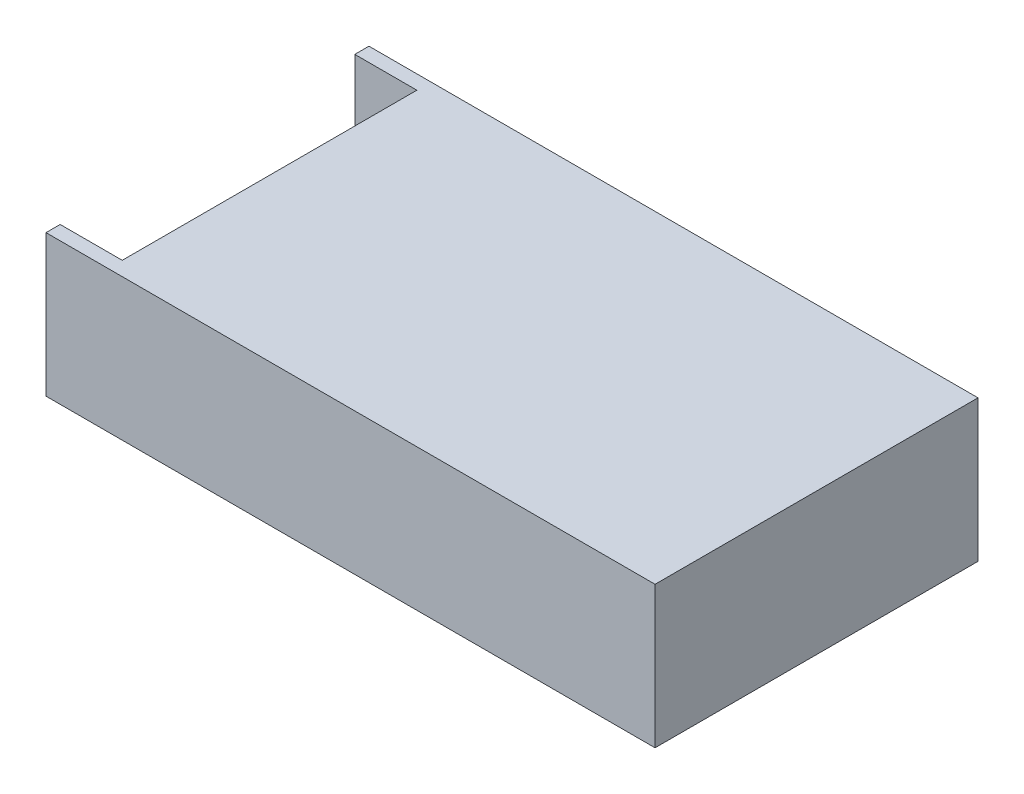
SolidWorks part; units mm, degrees
ref_plane "Plano frontal" through (0, 0, 0) normal (0, 0, 1) x (1, 0, 0)
ref_plane "Plano superior" through (0, 0, 0) normal (0, 1, 0) x (1, 0, 0)
ref_plane "Plano direito" through (0, 0, 0) normal (1, 0, 0) x (0, 0, -1)
sketch "Esboço1" plane through (0, 0, 0) normal (0, 1, 0) x (1, 0, 0)
  line L1 (-107.5, 57) -> (107.5, 57)
  line L2 (-107.5, 57) -> (-107.5, -57)
  line L3 (-107.5, -57) -> (107.5, -57)
  line L4 (107.5, 57) -> (107.5, -57)
  line L5 (-107.5, 57) -> (107.5, -57) construction
  line L6 (-107.5, -57) -> (107.5, 57) construction
  point P0 (0, 0)
  dimension "D1" = 215
  dimension "D2" = 114
extrude "Ressalto-extrusão1" add sketch "Esboço1" along normal blind 50
sketch "Esboço3" plane through (0, 0, 57) normal (0, 0, 1) x (1, 0, 0)
  line L1 (-107.5, 50) -> (-85.5852, 50)
  line L2 (-107.5, 50) -> (-107.5, 17.4571)
  line L3 (-102.4831, 16.1339) -> (-85.5852, 16.1339)
  line L4 (-85.5852, 50) -> (-85.5852, 16.1339)
  line L5 (-102.4831, 6.4269) -> (-107.5, 6.4269)
  line L6 (-102.4831, 6.4269) -> (-102.4831, 16.1339)
  line L8 (-107.5, 6.4269) -> (-107.5, 17.4571)
  point P6 (-98.3246, 16.1357)
  point P9 (-102.4831, 16.3956)
  point P10 (-86.534, 14.6225)
  point P11 (-95.4137, 22.195)
  point P12 (-85.5852, 16.1339)
extrude "Corte-extrusão1" cut sketch "Esboço3" against normal offset from surface (104 mm away) 5 from offset 5
